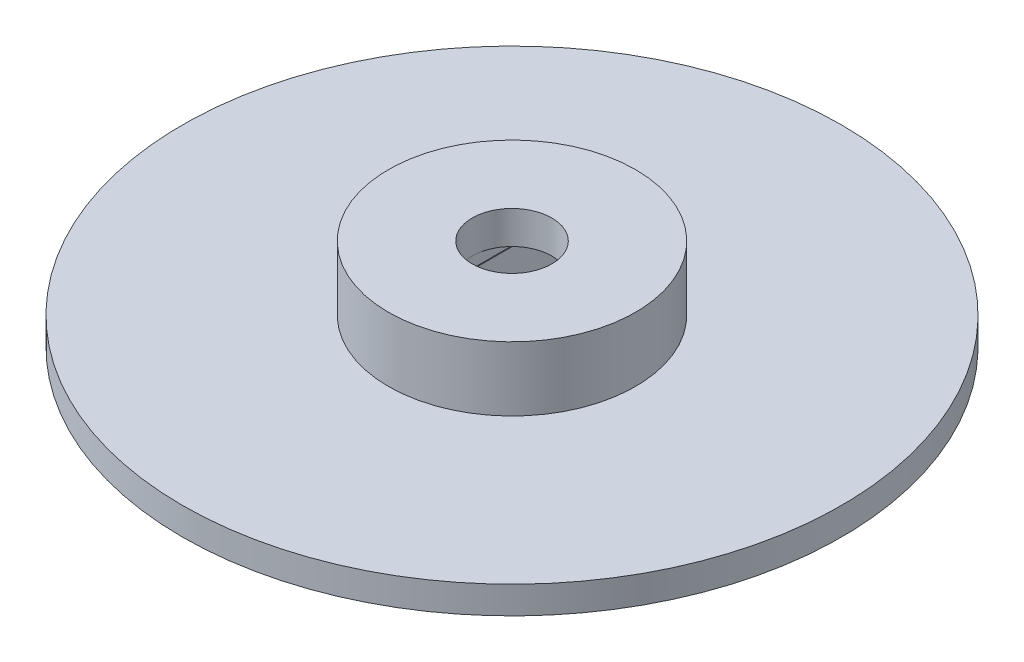
SolidWorks part; units mm, degrees
ref_plane "Front Plane" through (0, 0, 0) normal (0, 0, 1) x (1, 0, 0)
ref_plane "Top Plane" through (0, 0, 0) normal (0, 1, 0) x (1, 0, 0)
ref_plane "Right Plane" through (0, 0, 0) normal (1, 0, 0) x (0, 0, -1)
sketch "Sketch1" plane through (0, 0, 0) normal (0, 1, 0) x (1, 0, 0)
  circle A0 centre (0, 0) radius 60
  dimension "D1" = 120
extrude "Boss-Extrude1" add sketch "Sketch1" along normal blind 5
sketch "Sketch2" plane through (0, 5, 0) normal (0, 1, 0) x (1, 0, 0)
  circle A0 centre (0, 0) radius 22.5
  dimension "D1" = 45
extrude "Boss-Extrude3" add sketch "Sketch2" along normal blind 11.7
sketch "Sketch6" plane through (0, 16.7, 0) normal (0, 1, 0) x (1, 0, 0)
  circle A0 centre (0, 0) radius 7.25
  dimension "D1" = 14.5
extrude "Cut-Extrude4" cut sketch "Sketch6" against normal blind 6
sketch "Sketch7" plane through (0, 10.7, 0) normal (0, 1, 0) x (1, 0, 0)
  line L1 (-7.25, 15.55) -> (7.25, 15.55)
  line L2 (-7.25, 15.55) -> (-7.25, -7.25)
  line L3 (-7.25, -7.25) -> (7.25, -7.25)
  line L4 (7.25, 15.55) -> (7.25, -7.25)
  circle A0 centre (0, 0) radius 7.25 construction
  circle A1 centre (0, 0) radius 7.25 construction
  dimension "D1" = 14.5
  dimension "D2" = 22.8
extrude "Cut-Extrude5" cut sketch "Sketch7" against normal blind 2
sketch "Sketch9" plane through (0, 8.7, 0) normal (0, 1, 0) x (1, 0, 0)
  line L1 (-7.0966, 20.05) -> (7.4034, 20.05)
  line L2 (-7.0966, 20.05) -> (-7.0966, -11.75)
  line L3 (-7.0966, -11.75) -> (7.4034, -11.75)
  line L4 (7.4034, 20.05) -> (7.4034, -11.75)
  circle A0 centre (0, 0) radius 7.25 construction
  dimension "D1" = 14.5
  dimension "D2" = 31.8
  dimension "D3" = 11.75
extrude "Cut-Extrude6" cut sketch "Sketch9" against normal blind 25
